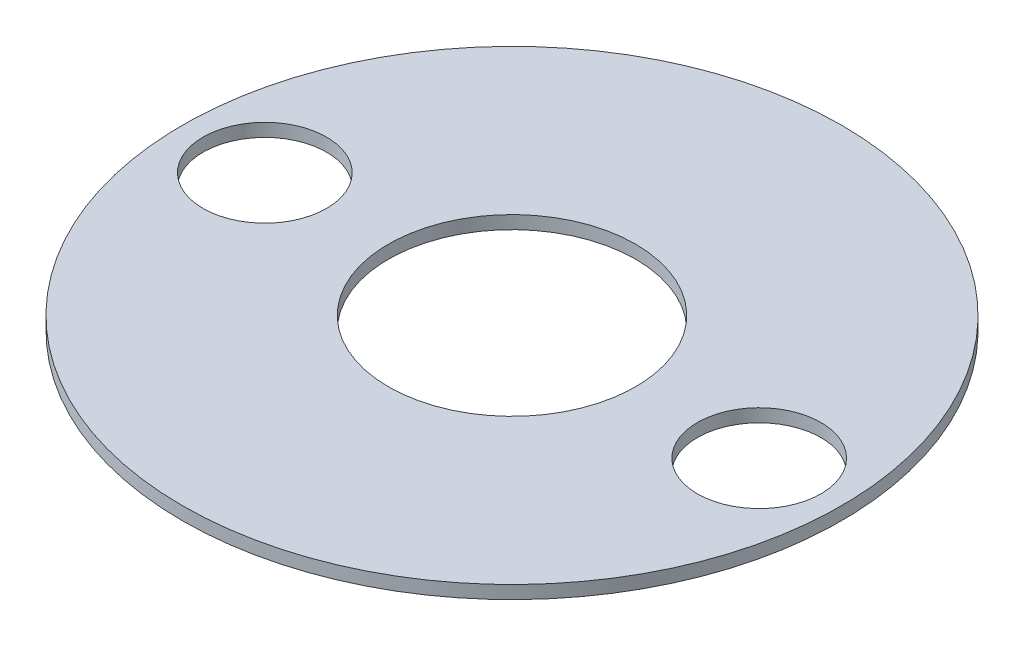
SolidWorks part; units mm, degrees
ref_plane "Front Plane" through (0, 0, 0) normal (0, 0, 1) x (1, 0, 0)
ref_plane "Top Plane" through (0, 0, 0) normal (0, 1, 0) x (1, 0, 0)
ref_plane "Right Plane" through (0, 0, 0) normal (1, 0, 0) x (0, 0, -1)
sketch "Sketch1" plane through (0, 0, 0) normal (0, 1, 0) x (1, 0, 0)
  circle A0 centre (0, 0) radius 7
  dimension "D1" = 14
extrude "Boss-Extrude1" add sketch "Sketch1" along normal blind 0.3175
sketch "Sketch2" plane through (0, 0.3175, 0) normal (0, 1, 0) x (1, 0, 0)
  circle A6 centre (0, 0) radius 8
  circle A7 centre (0, 0) radius 8
  point P13 (-18.9056, 0)
  point P14 (-25.4396, 0)
  dimension "D4" = 1
extrude "Boss-Extrude3" add sketch "Sketch2" against normal blind 0.3175
sketch "Sketch3" plane through (0, 0.3175, 0) normal (0, 1, 0) x (1, 0, 0)
  circle A0 centre (6, 0) radius 1.5 construction
  circle A1 centre (0, 0) radius 8
  circle A2 centre (0, 0) radius 8
  circle A3 centre (6, 0) radius 1.5
  circle A4 centre (6, 0) radius 1.5
  dimension "D2" = 3
  dimension "D1" = 0
extrude "Cut-Extrude2" cut sketch "Sketch3" against normal blind 0.3175
sketch "Sketch4" plane through (0, 0.3175, 0) normal (0, 1, 0) x (1, 0, 0)
  circle A0 centre (-6, 0) radius 1.5
  dimension "D1" = 3
extrude "Cut-Extrude3" cut sketch "Sketch4" against normal blind 0.3175
sketch "Sketch5" plane through (0, 0.3175, 0) normal (0, 1, 0) x (1, 0, 0)
  circle A0 centre (0, 0) radius 3
  dimension "D1" = 6
extrude "Cut-Extrude4" cut sketch "Sketch5" against normal blind 0.3175
